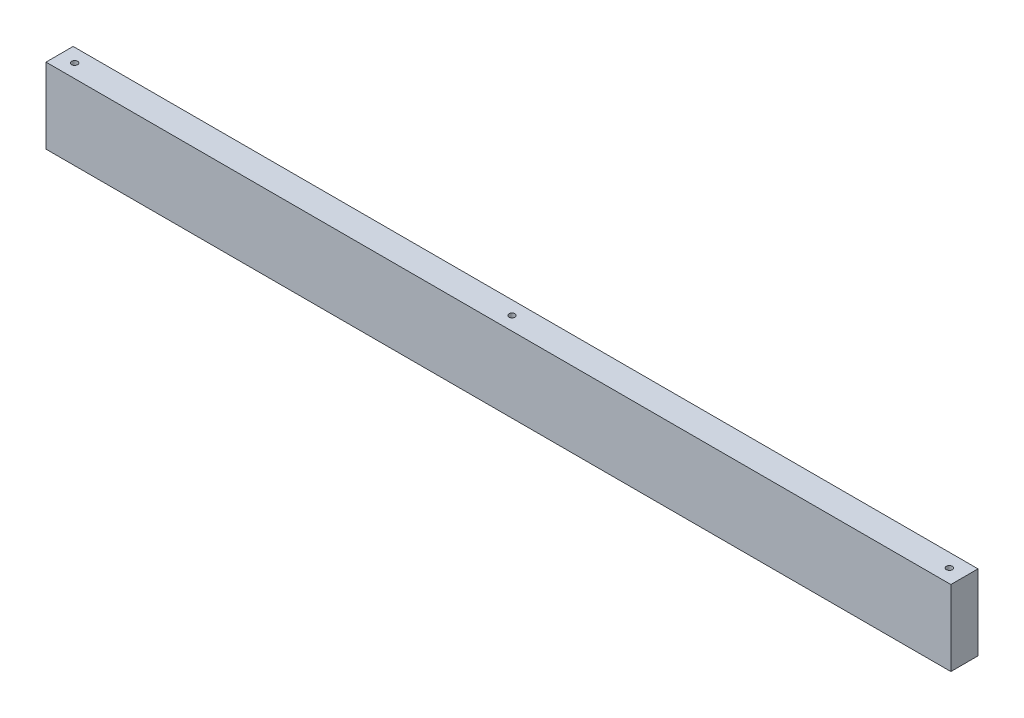
SolidWorks part; units mm, degrees
material "Mahogany"
ref_plane "Front Plane" through (0, 0, 0) normal (0, 0, 1) x (1, 0, 0)
ref_plane "Top Plane" through (0, 0, 0) normal (0, 1, 0) x (1, 0, 0)
ref_plane "Right Plane" through (0, 0, 0) normal (1, 0, 0) x (0, 0, -1)
sketch "Sketch1" plane through (0, 0, 0) normal (0, 0, 1) x (1, 0, 0)
  line L1 (-300, -25) -> (300, -25)
  line L2 (-300, -25) -> (-300, 25)
  line L3 (-300, 25) -> (300, 25)
  line L4 (300, -25) -> (300, 25)
  line L5 (-300, -25) -> (300, 25) construction
  line L6 (-300, 25) -> (300, -25) construction
  point P0 (0, 0)
  dimension "D1" = 600
  dimension "D2" = 50
extrude "Boss-Extrude1" add sketch "Sketch1" along normal blind 18
sketch "Sketch2" plane through (0, 25, 0) normal (0, 1, 0) x (1, 0, 0)
  line L0 (300, -18) -> (300, 0) construction
  line L1 (300, 0) -> (-300, 0) construction
  line L2 (300, -18) -> (-300, -18) construction
  line L3 (-300, -18) -> (-300, 0) construction
  circle A0 centre (-290, -9) radius 2
  circle A1 centre (0, -9) radius 2
  circle A2 centre (290, -9) radius 2
  dimension "D4" = 9
  dimension "D6" = 4
  dimension "D7" = 4
  dimension "D8" = 4
  dimension "D1" = 10
  dimension "D2" = 9
  dimension "D3" = 9
  dimension "D5" = 10
extrude "Cut-Extrude1" cut sketch "Sketch2" against normal blind 25
